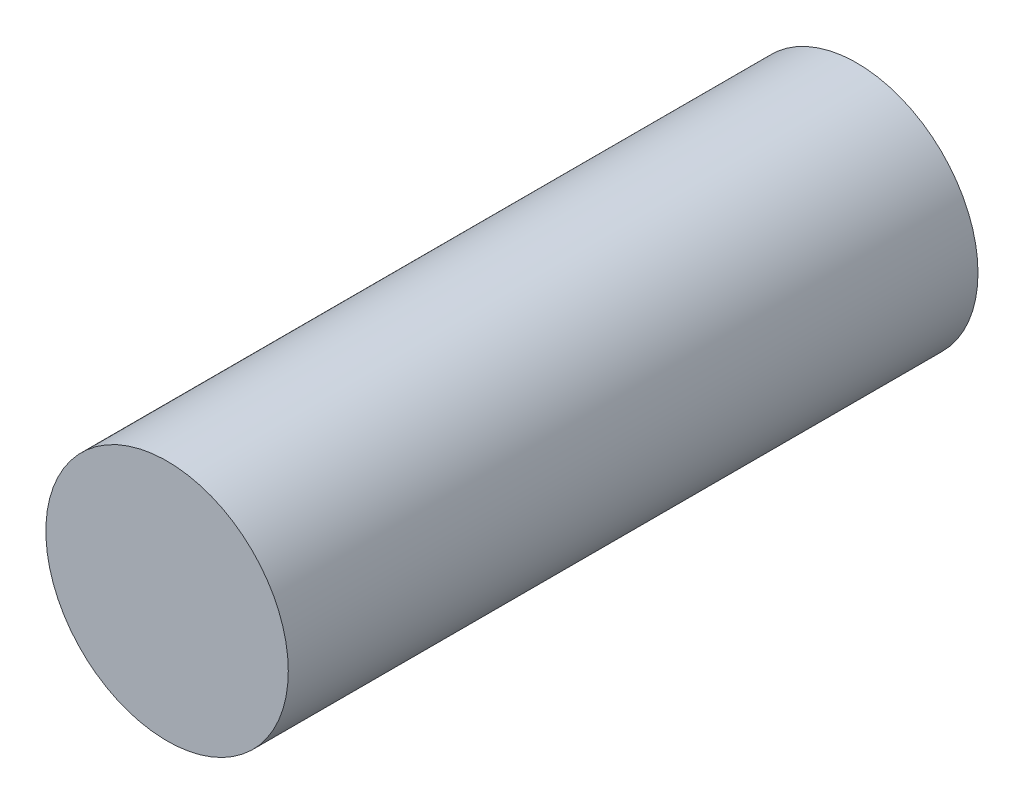
SolidWorks part; units mm, degrees
ref_plane "Front Plane" through (0, 0, 0) normal (0, 0, 1) x (1, 0, 0)
ref_plane "Top Plane" through (0, 0, 0) normal (0, 1, 0) x (1, 0, 0)
ref_plane "Right Plane" through (0, 0, 0) normal (1, 0, 0) x (0, 0, -1)
sketch "Sketch1" plane through (0, 0, 0) normal (0, 0, 1) x (1, 0, 0)
  circle A0 centre (0, 0) radius 12.5
  dimension "D1" = 25
extrude "Boss-Extrude1" add sketch "Sketch1" along normal blind 71.12
equation "\"D1@Sketch1\"=25mm"
